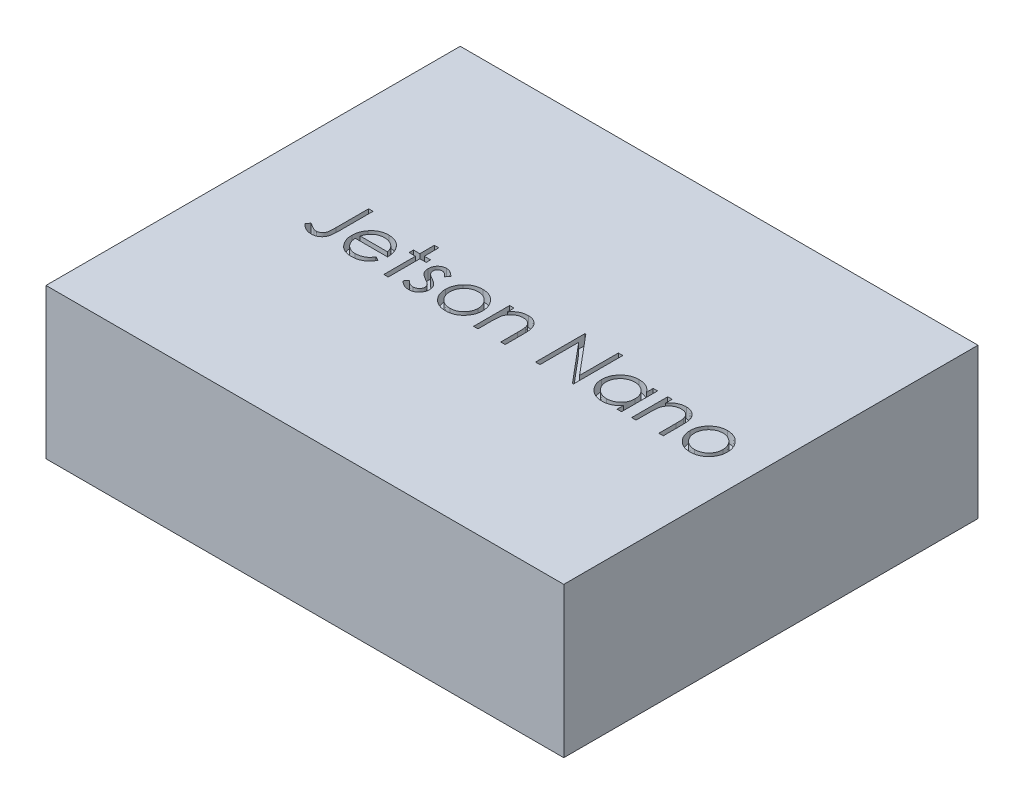
SolidWorks part; units mm, degrees
ref_plane "Front Plane" through (0, 0, 0) normal (0, 0, 1) x (1, 0, 0)
ref_plane "Top Plane" through (0, 0, 0) normal (0, 1, 0) x (1, 0, 0)
ref_plane "Right Plane" through (0, 0, 0) normal (1, 0, 0) x (0, 0, -1)
sketch "Sketch1" plane through (0, 0, 0) normal (0, 1, 0) x (1, 0, 0)
  line L1 (-50, -40) -> (50, -40)
  line L2 (-50, -40) -> (-50, 40)
  line L3 (-50, 40) -> (50, 40)
  line L4 (50, -40) -> (50, 40)
  line L5 (-50, -40) -> (50, 40) construction
  line L6 (-50, 40) -> (50, -40) construction
  point P0 (0, 0)
extrude "Boss-Extrude1" add sketch "Sketch1" along normal blind 29
sketch "Sketch2" plane through (0, 29, 0) normal (0, 1, 0) x (1, 0, 0)
  text T0 "Jetson Nano" font "Century Gothic" height in points 36
extrude "Cut-Extrude1" cut sketch "Sketch2" against normal blind 2
